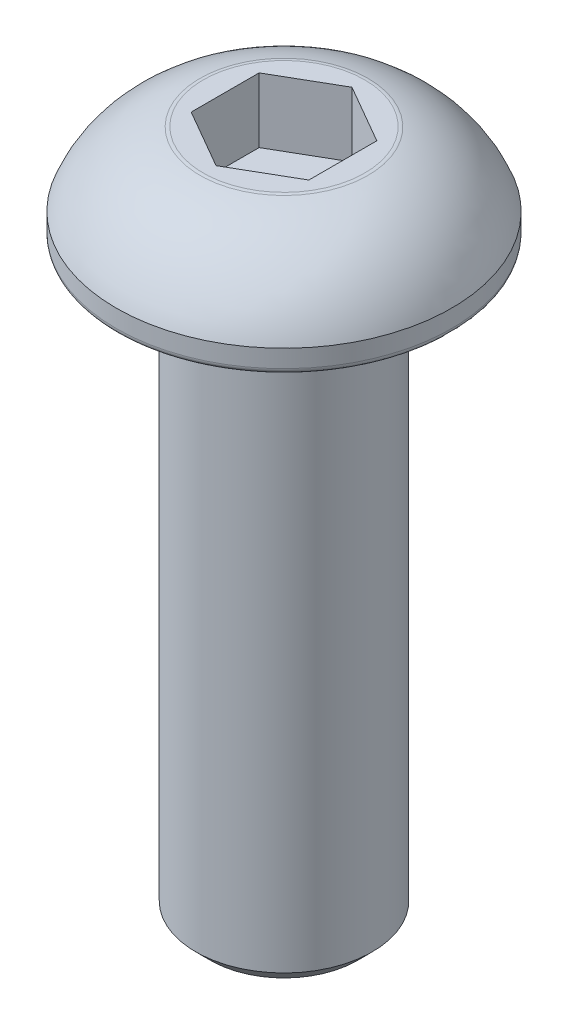
SolidWorks part; units mm, degrees
material "ASTM A36 Steel"
ref_plane "Front Plane" through (0, 0, 0) normal (0, 0, 1) x (1, 0, 0)
ref_plane "Top Plane" through (0, 0, 0) normal (0, 1, 0) x (1, 0, 0)
ref_plane "Right Plane" through (0, 0, 0) normal (1, 0, 0) x (0, 0, -1)
sketch "Sketch1" plane through (0, 0, 0) normal (0, 0, 1) x (1, 0, 0)
  line L7 (-1.5, -0.1) -> (-1.5, -9.75)
  line L8 (-1.25, -10) -> (0, -10)
  line L9 (0, -10) -> (0, 1.65)
  line L10 (-1.6, 0) -> (-2.75, 0)
  line L11 (-2.85, 0.1) -> (-2.85, 0.4)
  line L12 (-1.3725, 1.65) -> (0, 1.65)
  line L13 (-1.5, -9.75) -> (-1.25, -10)
  arc A0 (-2.85, 0.4) -> (-1.4287, 1.6436) centre (-0.9784, -0.3051) cw
  arc A3 (-2.75, 0) -> (-2.85, 0.1) centre (-2.75, 0.1) cw
  arc A4 (-1.4287, 1.6436) -> (-1.3725, 1.65) centre (-1.3725, 1.4) cw
  arc A5 (-1.5, -0.1) -> (-1.6, 0) centre (-1.6, -0.1) ccw
  point P1 (-1.5, -10)
  point P21 (-1.4, 1.65)
  point P24 (-1.5, 0)
  dimension "D1" = 1.5
  dimension "D7" = 2
  dimension "D8" = 0.1
  dimension "D9" = 0.25
  dimension "D10" = 0.1
  dimension "D2" = 2.85
  dimension "D4" = 1.4
  dimension "D5" = 1.65
  dimension "D6" = 0.4
  dimension "D11" = 10
revolve "Revolve1" add sketch "Sketch1" angle 360 about L9
sketch "Sketch2" plane through (0, 1.65, 0) normal (0, 1, 0) x (1, 0, 0)
  line L1 (-1, 0.5774) -> (-1, -0.5774)
  line L2 (-1, -0.5774) -> (0, -1.1547)
  line L3 (0, -1.1547) -> (1, -0.5774)
  line L4 (1, -0.5774) -> (1, 0.5774)
  line L5 (1, 0.5774) -> (0, 1.1547)
  line L6 (0, 1.1547) -> (-1, 0.5774)
  circle A0 centre (0, 0) radius 1 construction
  dimension "D1" = 2
extrude "Cut-Extrude1" cut sketch "Sketch2" against normal blind 1.1
